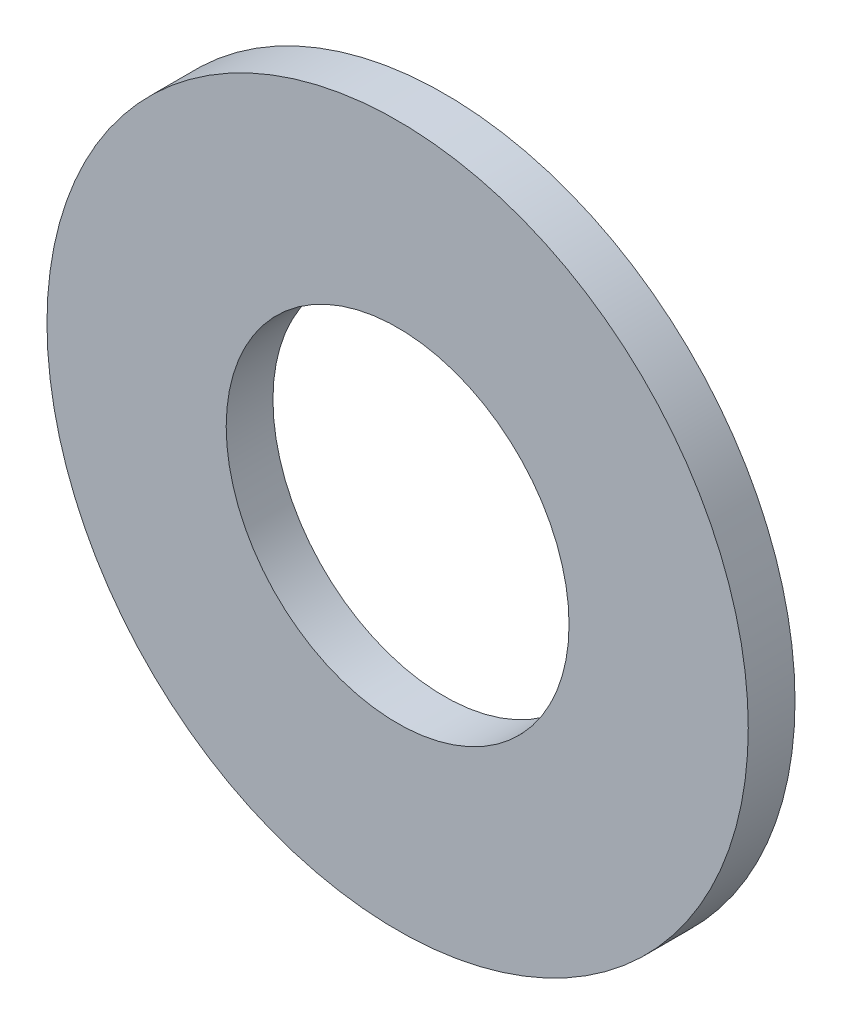
SolidWorks part; units mm, degrees
ref_plane "Front Plane" through (0, 0, 0) normal (0, 0, 1) x (1, 0, 0)
ref_plane "Top Plane" through (0, 0, 0) normal (0, 1, 0) x (1, 0, 0)
ref_plane "Right Plane" through (0, 0, 0) normal (1, 0, 0) x (0, 0, -1)
sketch "Sketch1" plane through (0, 0, 0) normal (0, 0, 1) x (1, 0, 0)
  circle A0 centre (0, 0) radius 2.25 construction
  circle A1 centre (0, 0) radius 1.1 construction
  point P5 (-1.1, 0)
  point P6 (1.1, 0)
  point P7 (2.25, 0)
  point P8 (-2.25, 0)
  point P9 (0, 0)
  point P10 (0, -1.1)
  dimension "OD" = 4.5
  dimension "ID" = 2.2
sketch "Sketch2" plane through (0, 0, 0) normal (1, 0, 0) x (0, 0, -1)
  line L0 (0, 2.25) -> (0, -2.25) construction
  line L1 (0, 2.25) -> (0, -2.25) construction
  line L2 (-0.15, 2.25) -> (0.15, 2.25) construction
  line L3 (-0.15, 0) -> (0.15, 0) construction
  line L4 (-0.15, -2.25) -> (0.15, -2.25) construction
  line L5 (0.15, -2.25) -> (0.15, 2.25) construction
  line L6 (-0.15, -2.25) -> (-0.15, 2.25) construction
  point P5 (0, 2.25)
  point P8 (0, 0)
  point P11 (0, -2.25)
  point P12 (0.15, 2.25)
  point P13 (0.15, 0)
  point P14 (0.15, -2.25)
  point P15 (-0.15, -2.25)
  point P16 (-0.15, 0)
  point P17 (-0.15, 2.25)
  dimension "Thickness Range" = 0.3
sketch "Sketch3" plane through (0, 0, 0) normal (0, 0, 1) x (1, 0, 0)
  circle A0 centre (0, 0) radius 2.25 construction
  circle A1 centre (0, 0) radius 1.1 construction
  circle A2 centre (0, 0) radius 2.25
  circle A3 centre (0, 0) radius 1.1
extrude "Boss-Extrude1" add sketch "Sketch3" along normal mid plane 0.3
equation "\"D1@Boss-Extrude1\" = \"Thickness Range@Sketch2\""
